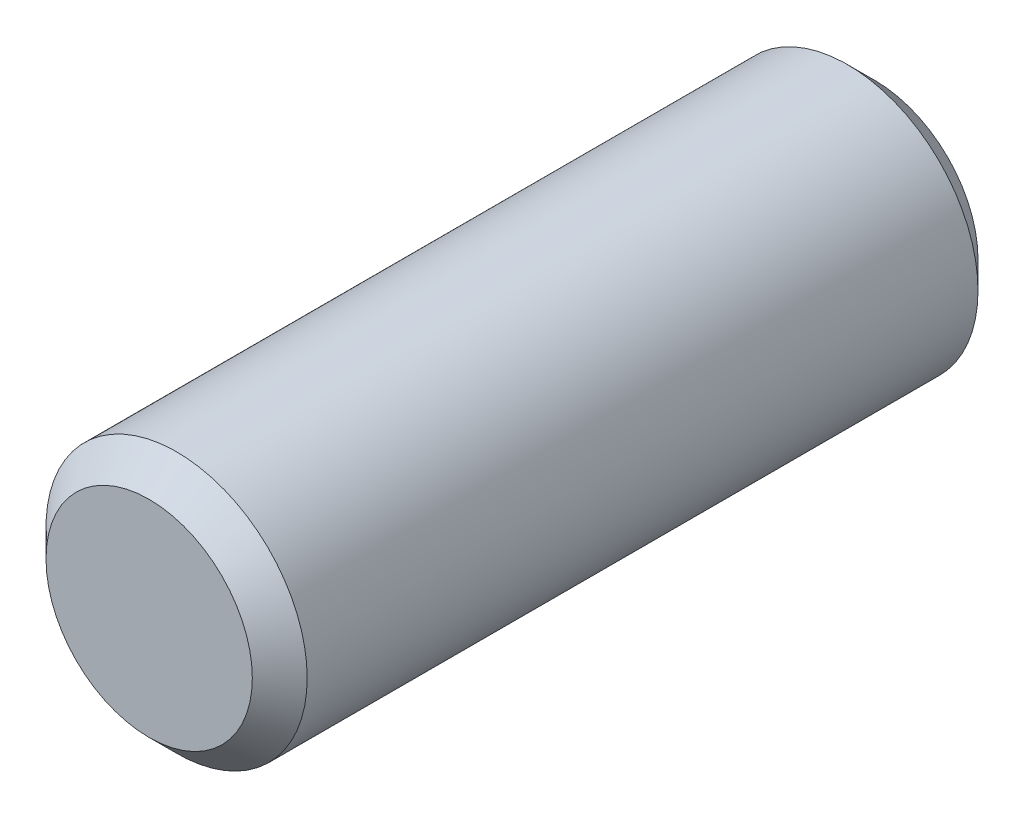
SolidWorks part; units mm, degrees
ref_plane "Front Plane" through (0, 0, 0) normal (0, 0, 1) x (1, 0, 0)
ref_plane "Top Plane" through (0, 0, 0) normal (0, 1, 0) x (1, 0, 0)
ref_plane "Right Plane" through (0, 0, 0) normal (1, 0, 0) x (0, 0, -1)
sketch "Sketch1" plane through (0, 0, 0) normal (0, 0, 1) x (1, 0, 0)
  circle A0 centre (0, 0) radius 9.52
  dimension "D1" = 19.04
extrude "Boss-Extrude1" add sketch "Sketch1" along normal mid plane 52.9
chamfer "Chamfer1" distance 2 angle 45 2 edges at (9.52, 0, -26.45) (9.52, 0, 26.45)
